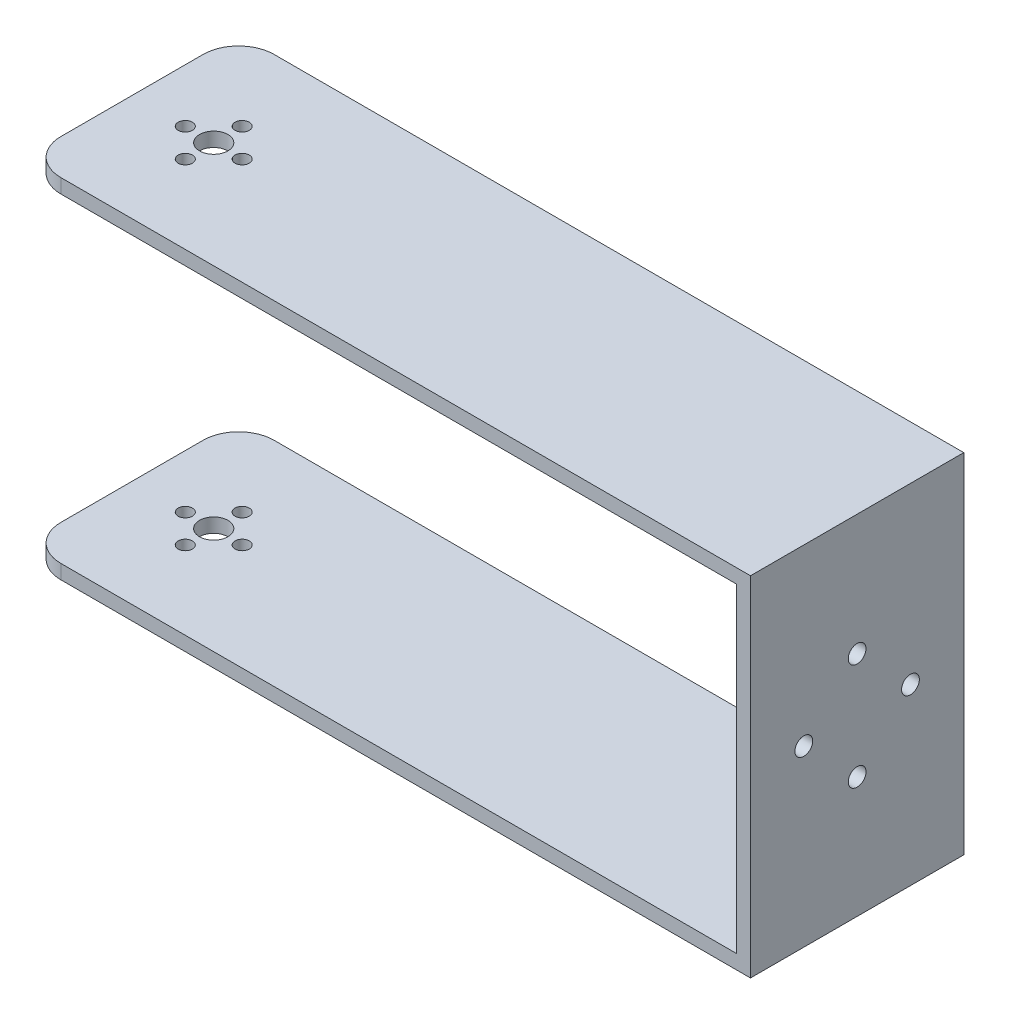
SolidWorks part; units mm, degrees
ref_plane "Ön Düzlem" through (0, 0, 0) normal (0, 0, 1) x (1, 0, 0)
ref_plane "Üst Düzlem" through (0, 0, 0) normal (0, 1, 0) x (1, 0, 0)
ref_plane "Sağ Düzlem" through (0, 0, 0) normal (1, 0, 0) x (0, 0, -1)
sketch "Çizim1" plane through (0, 0, 0) normal (0, 0, 1) x (1, 0, 0)
  line L0 (0, 0) -> (200, 0)
  line L1 (200, 0) -> (200, 90)
  line L2 (200, 90) -> (0, 90)
  dimension "D1" = 90
  dimension "D2" = 200
extrude "Ekstrüzyon-İnce1" add sketch "Çizim1" along normal blind 60 thin
fillet "Radyus1" radius 10 4 edges at (0, -2, 60) (0, -2, 0) (0, 92, 0) (0, 92, 60)
sketch "Çizim2" plane through (0, 94, 0) normal (0, 1, 0) x (1, 0, 0)
  line L0 (0, -50) -> (0, -10) construction
  circle A0 centre (23, -30) radius 4
  circle A1 centre (23, -22) radius 2
  circle A2 centre (23, -38) radius 2
  circle A3 centre (31, -30) radius 2
  circle A4 centre (15, -30) radius 2
  dimension "D1" = 8
  dimension "D3" = 4
  dimension "D5" = 4
  dimension "D6" = 15
  dimension "D7" = 8
  dimension "D8" = 8
  dimension "D2" = 8
  dimension "D4" = 8
extrude "Kes-Ekstrüzyon1" cut sketch "Çizim2" against normal up to next
ref_plane "Düzlem1" through (0, 45, 0) normal (0, 1, 0) x (1, 0, 0)
mirror "Aynalama1" about plane through (0, 45, 0) normal (0, 1, 0) of "Kes-Ekstrüzyon1"
sketch "Çizim3" plane through (204, 0, 0) normal (1, 0, 0) x (0, 0, -1)
  circle A0 centre (-30, 60) radius 2.5
  circle A1 centre (-30, 30) radius 2.5
  circle A2 centre (-15, 45) radius 2.5
  circle A3 centre (-45, 45) radius 2.5
  dimension "D1" = 5
  dimension "D3" = 5
  dimension "D4" = 30
  dimension "D2" = 30
extrude "Kes-Ekstrüzyon2" cut sketch "Çizim3" against normal up to next
